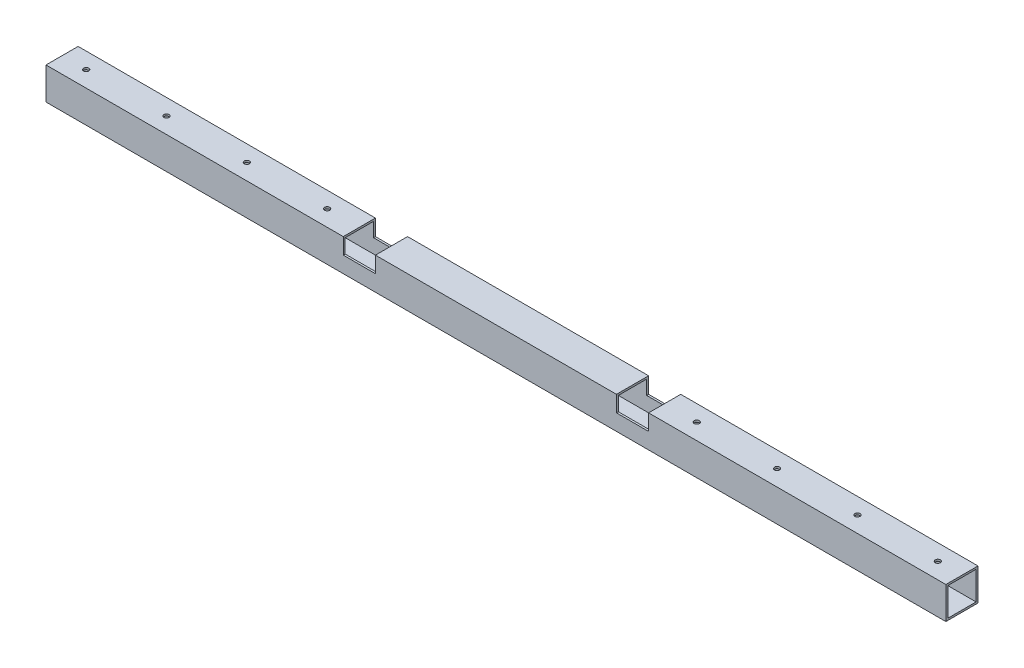
SolidWorks part; units mm, degrees
material "6061 合金"
ref_plane "前视基准面" through (0, 0, 0) normal (0, 0, 1) x (1, 0, 0)
ref_plane "上视基准面" through (0, 0, 0) normal (0, 1, 0) x (1, 0, 0)
ref_plane "右视基准面" through (0, 0, 0) normal (1, 0, 0) x (0, 0, -1)
sketch "草图1" plane through (0, 0, 0) normal (1, 0, 0) x (0, 0, -1)
  line L0 (-10, 10) -> (-10, -10)
  line L1 (-8.8, 8.8) -> (8.8, 8.8)
  line L2 (-8.8, 8.8) -> (-8.8, -8.8)
  line L3 (-8.8, -8.8) -> (8.8, -8.8)
  line L4 (8.8, 8.8) -> (8.8, -8.8)
  line L5 (-8.8, 8.8) -> (8.8, -8.8) construction
  line L6 (-8.8, -8.8) -> (8.8, 8.8) construction
  line L7 (-10, -10) -> (10, -10)
  line L8 (10, 10) -> (10, -10)
  line L9 (-10, 10) -> (10, 10)
  point P0 (0, 0)
  dimension "D1" = 1.2
  dimension "D2" = 20
  dimension "D3" = 20
extrude "凸台-拉伸1" add sketch "草图1" along normal mid plane 560
sketch "草图2" plane through (0, 0, -10) normal (0, 0, -1) x (-1, 0, 0)
  line L0 (0, 113.7589) -> (0, -114.3891) construction
  line L2 (-95, 10) -> (-75, 10)
  line L3 (-95, 10) -> (-95, 0)
  line L4 (-95, 0) -> (-75, 0)
  line L5 (-75, 10) -> (-75, 0)
  line L6 (-95, 10) -> (-75, 0) construction
  line L7 (-95, 0) -> (-75, 10) construction
  line L8 (-280, -10) -> (-280, 10) construction
  line L9 (95, 0) -> (75, 0)
  line L10 (75, 10) -> (75, 0)
  line L11 (95, 10) -> (75, 10)
  line L12 (95, 10) -> (95, 0)
  line L13 (-280, 10) -> (280, 10) construction
  point P3 (-85, 5)
  dimension "D1" = 20
  dimension "D2" = 185
  dimension "D3" = 10
extrude "切除-拉伸1" cut sketch "草图2" against normal through all
sketch "草图3" plane through (0, 10, 0) normal (0, 1, 0) x (1, 0, 0)
  line L0 (280, 0) -> (-280, 0) construction
  line L1 (280, 10) -> (280, -10) construction
  line L2 (-280, 10) -> (-280, -10) construction
  line L3 (0, -81.1519) -> (0, 80.1636) construction
  line L5 (95, -10) -> (75, -10) construction
  line L6 (95, -10) -> (75, -10) construction
  line L7 (85, -10) -> (85, 15.9167) construction
  circle A1 centre (115, 0) radius 1.6
  circle A2 centre (165, 0) radius 1.6
  circle A3 centre (265, 0) radius 1.6
  circle A4 centre (215, 0) radius 1.6
  circle A5 centre (-215, 0) radius 1.6
  circle A6 centre (-265, 0) radius 1.6
  circle A8 centre (-115, 0) radius 1.6
  circle A10 centre (85, 0) radius 1.6 construction
  circle A11 centre (-85, 0) radius 1.6 construction
  circle A13 centre (-165, 0) radius 1.6
  circle A14 centre (70, 0) radius 1.6 construction
  circle A15 centre (-70, 0) radius 1.6 construction
  circle A16 centre (40, 0) radius 1.6 construction
  circle A17 centre (-40, 0) radius 1.6 construction
  dimension "D1" = 3.2
  dimension "D7" = 3.2
  dimension "D8" = 30
  dimension "D9" = 50
  dimension "D5" = 15
  dimension "D2" = 50
  dimension "D3" = 50
  dimension "D4" = 15
  dimension "D6" = 50
extrude "切除-拉伸2" cut sketch "草图3" against normal through all
sketch "草图4" plane through (0, -10, 0) normal (0, -1, 0) x (1, 0, 0)
  line L0 (265, 0) -> (215, 0) construction
  line L1 (0, 70.5741) -> (0, -43.0546) construction
  line L2 (240, 0) -> (190, 0) construction
  circle A0 centre (240, 0) radius 2.5
  circle A1 centre (-240, 0) radius 2.5
  circle A2 centre (190, 0) radius 2.5
  circle A3 centre (140, 0) radius 2.5
  circle A4 centre (-140, 0) radius 2.5
  circle A5 centre (-190, 0) radius 2.5
  dimension "D1" = 5
  dimension "D2" = 3
  dimension "D3" = 50
extrude "切除-拉伸3" cut sketch "草图4" against normal up to next
